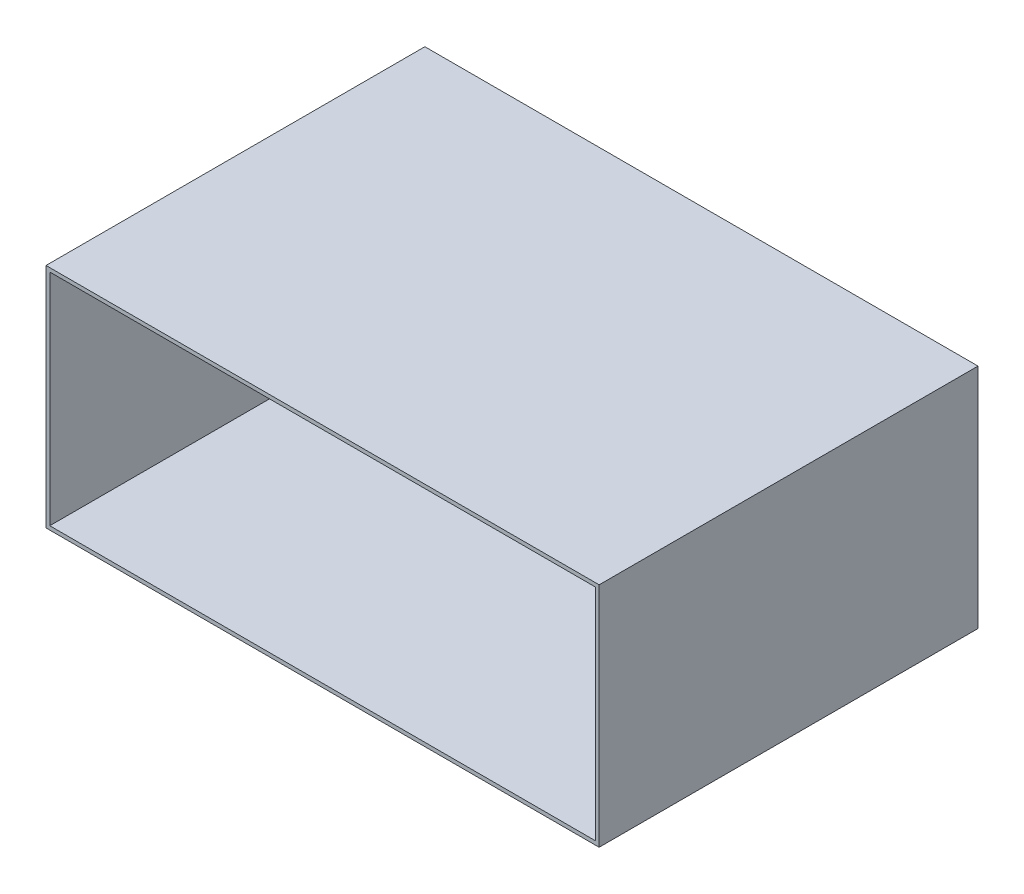
SolidWorks part; units mm, degrees
ref_plane "Front Plane" through (0, 0, 0) normal (0, 0, 1) x (1, 0, 0)
ref_plane "Top Plane" through (0, 0, 0) normal (0, 1, 0) x (1, 0, 0)
ref_plane "Right Plane" through (0, 0, 0) normal (1, 0, 0) x (0, 0, -1)
sketch "Sketch1" plane through (0, 0, 0) normal (0, 0, 1) x (1, 0, 0)
  line L0 (-6.2618, 34.233) -> (-78.2618, 34.233)
  line L1 (-78.2618, 34.233) -> (-78.2618, 63.233)
  line L2 (-78.2618, 63.233) -> (-6.2618, 63.233)
  line L3 (-6.2618, 63.233) -> (-6.2618, 34.233)
  line L4 (-5.7618, 33.733) -> (-78.7618, 33.733)
  line L5 (-78.7618, 33.733) -> (-78.7618, 63.733)
  line L6 (-78.7618, 63.733) -> (-5.7618, 63.733)
  line L7 (-5.7618, 63.733) -> (-5.7618, 33.733)
  dimension "D1" = 0.5
extrude "Boss-Extrude1" add sketch "Sketch1" along normal blind 50 contours L2 L3 L0 L1
